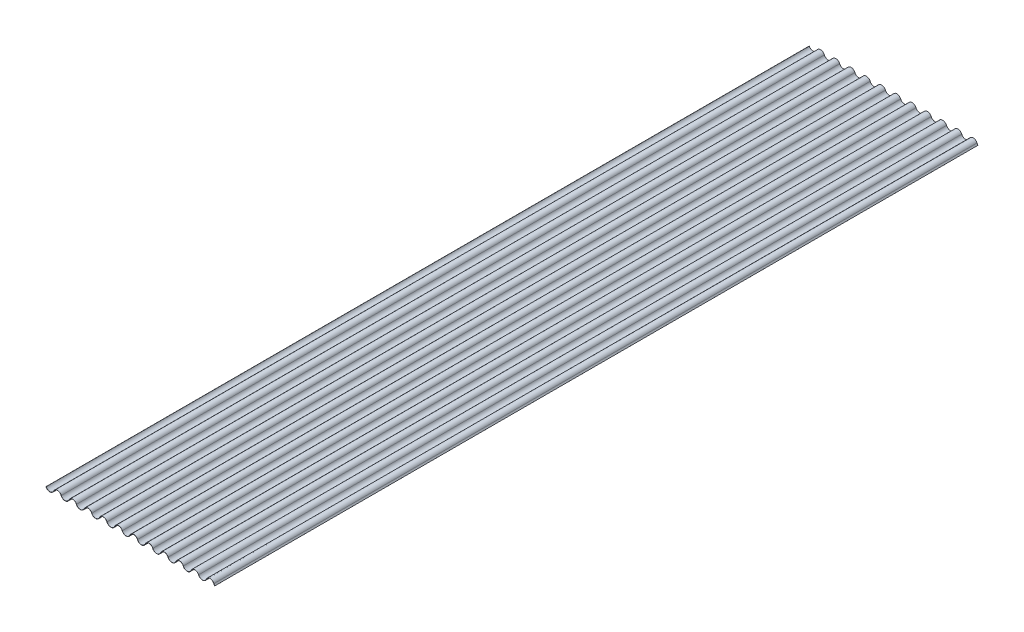
SolidWorks part; units mm, degrees
material "Liga de zinco 7; AG40B; Zn-4Al-0.015Mg"
ref_plane "Plano frontal" through (0, 0, 0) normal (0, 0, 1) x (1, 0, 0)
ref_plane "Plano superior" through (0, 0, 0) normal (0, 1, 0) x (1, 0, 0)
ref_plane "Plano direito" through (0, 0, 0) normal (1, 0, 0) x (0, 0, -1)
sketch "Esboço1" plane through (0, 0, 0) normal (0, 0, 1) x (1, 0, 0)
  line L3 (-1050, 0) -> (-1048.9063, 0.5393) construction
  line L4 (-1000, 0) -> (-999.0741, -0.3777) construction
  line L5 (-975, 36.443) -> (-975, -21.3468) construction
  line L6 (25, 25.564) -> (25, -13.2906) construction
  line L8 (-1050, 0) -> (-1048.9063, 0.5393)
  line L9 (55.8167, -10.198) -> (56.5018, -9.4696)
  arc A2 (-950, 0) -> (-900, 0) centre (-925, 10.198) ccw
  arc A3 (-1000, 0) -> (-950, 0) centre (-975, -10.198) cw
  arc A4 (-850, 0) -> (-800, 0) centre (-825, 10.198) ccw
  arc A5 (-900, 0) -> (-850, 0) centre (-875, -10.198) cw
  arc A6 (-750, 0) -> (-700, 0) centre (-725, 10.198) ccw
  arc A7 (-800, 0) -> (-750, 0) centre (-775, -10.198) cw
  arc A8 (-650, 0) -> (-600, 0) centre (-625, 10.198) ccw
  arc A9 (-700, 0) -> (-650, 0) centre (-675, -10.198) cw
  arc A10 (-550, 0) -> (-500, 0) centre (-525, 10.198) ccw
  arc A11 (-600, 0) -> (-550, 0) centre (-575, -10.198) cw
  arc A12 (-450, 0) -> (-400, 0) centre (-425, 10.198) ccw
  arc A13 (-500, 0) -> (-450, 0) centre (-475, -10.198) cw
  arc A14 (-350, 0) -> (-300, 0) centre (-325, 10.198) ccw
  arc A15 (-400, 0) -> (-350, 0) centre (-375, -10.198) cw
  arc A16 (-250, 0) -> (-200, 0) centre (-225, 10.198) ccw
  arc A17 (-300, 0) -> (-250, 0) centre (-275, -10.198) cw
  arc A18 (-150, 0) -> (-100, 0) centre (-125, 10.198) ccw
  arc A19 (-200, 0) -> (-150, 0) centre (-175, -10.198) cw
  arc A20 (-50, 0) -> (0, 0) centre (-25, 10.198) ccw
  arc A21 (-100, 0) -> (-50, 0) centre (-75, -10.198) cw
  arc A24 (-999.0741, -0.3777) -> (-950.9259, -0.3777) centre (-975, -10.198) cw
  arc A25 (-950.9259, -0.3777) -> (-899.0741, -0.3777) centre (-925, 10.198) ccw
  arc A26 (-899.0741, -0.3777) -> (-850.9259, -0.3777) centre (-875, -10.198) cw
  arc A27 (-850.9259, -0.3777) -> (-799.0741, -0.3777) centre (-825, 10.198) ccw
  arc A28 (-799.0741, -0.3777) -> (-750.9259, -0.3777) centre (-775, -10.198) cw
  arc A29 (-750.9259, -0.3777) -> (-699.0741, -0.3777) centre (-725, 10.198) ccw
  arc A30 (-699.0741, -0.3777) -> (-650.9259, -0.3777) centre (-675, -10.198) cw
  arc A31 (-650.9259, -0.3777) -> (-599.0741, -0.3777) centre (-625, 10.198) ccw
  arc A32 (-599.0741, -0.3777) -> (-550.9259, -0.3777) centre (-575, -10.198) cw
  arc A33 (-550.9259, -0.3777) -> (-499.0741, -0.3777) centre (-525, 10.198) ccw
  arc A34 (-499.0741, -0.3777) -> (-450.9259, -0.3777) centre (-475, -10.198) cw
  arc A35 (-450.9259, -0.3777) -> (-399.0741, -0.3777) centre (-425, 10.198) ccw
  arc A36 (-399.0741, -0.3777) -> (-350.9259, -0.3777) centre (-375, -10.198) cw
  arc A37 (-350.9259, -0.3777) -> (-299.0741, -0.3777) centre (-325, 10.198) ccw
  arc A38 (-299.0741, -0.3777) -> (-250.9259, -0.3777) centre (-275, -10.198) cw
  arc A39 (-250.9259, -0.3777) -> (-199.0741, -0.3777) centre (-225, 10.198) ccw
  arc A40 (-199.0741, -0.3777) -> (-150.9259, -0.3777) centre (-175, -10.198) cw
  arc A41 (-150.9259, -0.3777) -> (-99.0741, -0.3777) centre (-125, 10.198) ccw
  arc A42 (-99.0741, -0.3777) -> (-50.9259, -0.3777) centre (-75, -10.198) cw
  arc A43 (-50.9259, -0.3777) -> (0.9259, -0.3777) centre (-25, 10.198) ccw
  arc A44 (-1099.0741, -0.3777) -> (-1050.9259, -0.3777) centre (-1075, -10.198) cw construction
  arc A46 (-1050, 0) -> (-1000, 0) centre (-1025, 10.198) ccw construction
  arc A47 (-1050.9259, -0.3777) -> (-999.0741, -0.3777) centre (-1025, 10.198) ccw construction
  arc A48 (-1048.9063, 0.5393) -> (-1000, 0) centre (-1024.3338, 11.0868) ccw
  arc A49 (-1050, 0) -> (-999.0741, -0.3777) centre (-1024.4532, 11.1175) ccw
  arc A50 (50, 0) -> (0, 0) centre (25, -10.198) ccw
  arc A51 (49.0741, -0.3777) -> (0.9259, -0.3777) centre (25, -10.198) ccw
  arc A52 (-1100, 0) -> (-1050, 0) centre (-1075, -10.198) cw construction
  arc A53 (55.8167, -10.198) -> (49.0741, -0.3777) centre (75, 10.198) cw
  arc A54 (56.5018, -9.4696) -> (50, 0) centre (75, 10.198) cw
  dimension "D1" = 1
  dimension "D3" = 50
extrude "Ressalto-extrusão1" add sketch "Esboço1" along normal blind 5000
